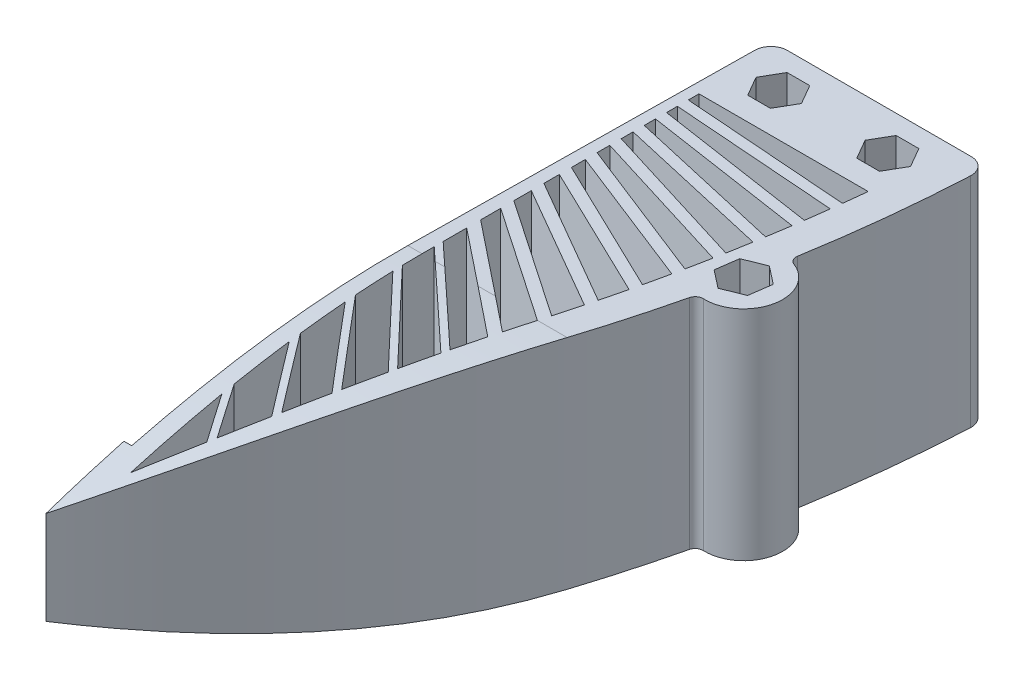
SolidWorks part; units mm, degrees
material "6061 合金"
ref_plane "前视基准面" through (0, 0, 0) normal (0, 0, 1) x (1, 0, 0)
ref_plane "上视基准面" through (0, 0, 0) normal (0, 1, 0) x (1, 0, 0)
ref_plane "右视基准面" through (0, 0, 0) normal (1, 0, 0) x (0, 0, -1)
other "Configuration Table"
sketch "草图3" plane through (0, 0, 0) normal (0, 1, 0) x (1, 0, 0)
  line B0 (0, 120.3647) -> (0, 1)
  line B1 (36.724, 123.3647) -> (3, 123.3647)
  line B2 (6.4046, 13.5169) -> (1.8, 20.8875)
  line B3 (1.8, 20.8875) -> (1.8, 4.167)
  line B4 (10.1087, 21.7103) -> (1.8, 33.2384)
  line B5 (1.8, 23.1524) -> (7.0103, 14.8122)
  line B6 (1.8, 33.2384) -> (1.8, 23.1524)
  line B7 (13.3609, 29.5129) -> (1.8, 43.5031)
  line B8 (1.8, 35.2908) -> (10.6622, 22.9946)
  line B9 (1.8, 43.5031) -> (1.8, 35.2908)
  line B10 (16.224, 36.9613) -> (1.8, 52.2374)
  line B11 (1.8, 45.3869) -> (13.8664, 30.785)
  line B12 (1.8, 52.2374) -> (1.8, 45.3869)
  line B13 (18.7509, 44.0926) -> (1.8, 59.8201)
  line B14 (1.8, 53.9853) -> (16.6853, 38.2206)
  line B15 (1.8, 59.8201) -> (1.8, 53.9853)
  line B16 (20.8682, 50.5668) -> (1.8, 65.7724)
  line B17 (1.8, 61.457) -> (19.1715, 45.3393)
  line B18 (1.8, 65.7724) -> (1.8, 61.457)
  line B19 (22.9742, 57.5717) -> (1.8, 72.0074)
  line B20 (1.8, 68.3304) -> (21.5044, 52.6174)
  line B21 (1.8, 72.0074) -> (1.8, 68.3304)
  line B22 (24.8276, 64.329) -> (1.8, 77.6234)
  line B23 (1.8, 74.4279) -> (23.5489, 59.6005)
  line B24 (1.8, 77.6234) -> (1.8, 74.4279)
  line B25 (26.4619, 70.8851) -> (1.8, 82.7612)
  line B26 (1.8, 79.9327) -> (25.3458, 66.3392)
  line B27 (1.8, 82.7612) -> (1.8, 79.9327)
  line B28 (27.9039, 77.2845) -> (1.8, 87.5291)
  line B29 (1.8, 84.981) -> (26.9277, 72.8807)
  line B30 (1.8, 87.5291) -> (1.8, 84.981)
  line B31 (29.1751, 83.5691) -> (1.8, 92.0128)
  line B32 (1.8, 89.6776) -> (28.3208, 79.2693)
  line B33 (1.8, 92.0128) -> (1.8, 89.6776)
  line B34 (30.2921, 89.7796) -> (1.8, 96.2825)
  line B35 (1.8, 94.1058) -> (29.5459, 85.5477)
  line B36 (1.8, 96.2825) -> (1.8, 94.1058)
  line B37 (31.2672, 95.956) -> (1.8, 100.3973)
  line B38 (1.8, 98.334) -> (30.6188, 91.7565)
  line B39 (1.8, 100.3973) -> (1.8, 98.334)
  line B40 (32.1089, 102.1377) -> (1.8, 104.409)
  line B41 (1.8, 102.4199) -> (31.5513, 97.9358)
  line B42 (1.8, 104.409) -> (1.8, 102.4199)
  line B43 (32.8223, 108.3647) -> (1.8, 108.3647)
  line B44 (1.8, 106.4146) -> (32.3512, 104.1252)
  line B45 (1.8, 108.3647) -> (1.8, 106.4146)
  line B46 (1.8, 110.3647) -> (33.0229, 110.3647)
  line B47 (1.8, 113.3647) -> (1.8, 110.3647)
  line B48 (33.298, 113.3647) -> (1.8, 113.3647)
  arc B49 (1.8, 4.167) -> (6.4046, 13.5169) centre (-259.6074, 138.7114) ccw
  arc B50 (7.0103, 14.8122) -> (10.1087, 21.7103) centre (-259.6074, 138.7114) ccw
  arc B51 (10.6622, 22.9946) -> (13.3609, 29.5129) centre (-259.6074, 138.7114) ccw
  arc B52 (0, 1) -> (1.8457, 0.4664) centre (1, 1) ccw
  arc B53 (1.8457, 0.4664) -> (33.5274, 76.1799) centre (-207.4276, 132.52) ccw
  arc B54 (35.9053, 78.4473) -> (33.5274, 76.1799) centre (36.4486, 75.4969) ccw
  arc B55 (35.9053, 78.4473) -> (37.7492, 87.541) centre (35, 83.3647) ccw
  arc B56 (36.4422, 90.5556) -> (37.7492, 87.541) centre (39.3987, 90.0468) ccw
  arc B57 (36.4422, 90.5556) -> (39.7203, 120.2155) centre (-207.4276, 132.52) ccw
  arc B58 (39.7203, 120.2155) -> (36.724, 123.3647) centre (36.724, 120.3647) ccw
  arc B59 (3, 123.3647) -> (0, 120.3647) centre (3, 120.3647) ccw
  arc B60 (13.8664, 30.785) -> (16.224, 36.9613) centre (-259.6074, 138.7114) ccw
  arc B61 (16.6853, 38.2206) -> (18.7509, 44.0926) centre (-259.6074, 138.7114) ccw
  arc B62 (19.1715, 45.3393) -> (20.8682, 50.5668) centre (-259.6074, 138.7114) ccw
  arc B63 (21.5044, 52.6174) -> (22.9742, 57.5717) centre (-259.6074, 138.7114) ccw
  arc B64 (23.5489, 59.6005) -> (24.8276, 64.329) centre (-259.6074, 138.7114) ccw
  arc B65 (25.3458, 66.3392) -> (26.4619, 70.8851) centre (-259.6074, 138.7114) ccw
  arc B66 (26.9277, 72.8807) -> (27.9039, 77.2845) centre (-259.6074, 138.7114) ccw
  arc B67 (28.3208, 79.2693) -> (29.1751, 83.5691) centre (-259.6074, 138.7114) ccw
  circle B68 centre (35, 83.3647) radius 2
  arc B69 (29.5459, 85.5477) -> (30.2921, 89.7796) centre (-259.6074, 138.7114) ccw
  arc B70 (30.6188, 91.7565) -> (31.2672, 95.956) centre (-259.6074, 138.7114) ccw
  arc B71 (31.5513, 97.9358) -> (32.1089, 102.1377) centre (-259.6074, 138.7114) ccw
  arc B72 (32.3512, 104.1252) -> (32.8223, 108.3647) centre (-259.6074, 138.7114) ccw
  arc B73 (33.0229, 110.3647) -> (33.298, 113.3647) centre (-259.6074, 138.7114) ccw
  circle B74 centre (35, 118.3647) radius 2
  circle B75 centre (5, 118.3647) radius 2
sketch_block_instance "umi-1"
sketch_block "umi"
extrude "凸台-拉伸2" add sketch "草图3" along normal blind 40
scale "缩放比例2" scale about centroid uniform scaling yes scale factor 0.7
sketch "草图7" plane through (0, 34, 0) normal (0, 1, 0) x (1, 0, 0)
  line L1 (3.2917, 19.3564) -> (3.2917, 29.3564)
  line L2 (3.2917, 29.3564) -> (4.2917, 29.3564)
  line L3 (4.2917, 29.3564) -> (5.2917, 108.3072)
  line L4 (5.2917, 108.3072) -> (5.2917, 24.752) construction
  line L5 (5.2917, 108.3072) -> (5.2917, 24.752)
  arc A0 (6.5837, 24.3784) -> (28.7609, 77.3779) centre (-139.9076, 116.816) ccw construction
  arc A1 (3.2917, 19.3564) -> (6.5837, 24.3784) centre (-139.9076, 116.816) ccw
  arc A4 (5.2917, 24.752) -> (6.5837, 24.3784) centre (5.9917, 24.752) ccw construction
  arc A5 (5.2917, 24.752) -> (6.5837, 24.3784) centre (5.9917, 24.752) ccw
  dimension "D1" = 2
  dimension "D2" = 1
  dimension "D3" = 10
extrude "凸台-拉伸3" add sketch "草图7" against normal up to surface (28 mm away) up to face at (17.3284, 6, -98.8239)
sketch "草图6" plane through (0, 34, 0) normal (0, 1, 0) x (1, 0, 0)
  circle A0 centre (8.7917, 106.9072) radius 1.5
  circle A1 centre (29.7917, 106.9072) radius 1.5
  circle A2 centre (29.7917, 82.4072) radius 1.5
  dimension "D1" = 3
  dimension "D2" = 3
  dimension "D3" = 3
extrude "切除-拉伸4" cut sketch "草图6" against normal blind 30
sketch "草图9" plane through (0, 34, 0) normal (0, 1, 0) x (1, 0, 0)
  circle A0 centre (29.7917, 106.9072) radius 1.5 construction
  circle A1 centre (8.7917, 106.9072) radius 1.5 construction
  circle A2 centre (29.7917, 106.9072) radius 1.5
  circle A3 centre (8.7917, 106.9072) radius 1.5
extrude "凸台-拉伸5" add sketch "草图9" against normal up to surface (28 mm away) up to face at (8.7917, 6, -105.4072)
sketch "草图17" plane through (0, 34, 0) normal (0, 1, 0) x (1, 0, 0)
  line L3 (28.6003, 103.4072) -> (6.5517, 103.4072)
  line L4 (6.5517, 101.3072) -> (28.4078, 101.3072)
  line L5 (6.5517, 103.4072) -> (6.5517, 101.3072)
  line L6 (28.6003, 103.4072) -> (6.5517, 103.4072)
  line L7 (6.5517, 101.3072) -> (28.4078, 101.3072)
  line L8 (6.5517, 103.4072) -> (6.5517, 101.3072)
  arc A0 (28.7956, 77.5075) -> (30.7828, 87.308) centre (29.7917, 82.4072) ccw
  arc A1 (28.4078, 101.3072) -> (28.6003, 103.4072) centre (-176.4334, 121.1499) ccw
  arc A2 (28.4078, 101.3072) -> (28.6003, 103.4072) centre (-176.4334, 121.1499) ccw
  arc A5 (30.4255, 78.9651) -> (28.7609, 77.3779) centre (30.8057, 76.8998) ccw construction
  arc A6 (30.4255, 78.9651) -> (31.7162, 85.3307) centre (29.7917, 82.4072) ccw construction
  arc A7 (30.8013, 87.4409) -> (31.7162, 85.3307) centre (32.8708, 87.0847) ccw construction
  arc A8 (30.4255, 78.9651) -> (28.7956, 77.5075) centre (30.8057, 76.8998) ccw
  arc A9 (30.4255, 78.9651) -> (31.7162, 85.3307) centre (29.7917, 82.4072) ccw
  arc A10 (30.7828, 87.308) -> (31.7162, 85.3307) centre (32.8708, 87.0847) ccw
  dimension "D2" = 10
  dimension "D1" = 0
extrude "凸台-拉伸6" add sketch "草图17" against normal up to surface (28 mm away)
sketch "草图12" plane through (0, 34, 0) normal (0, 1, 0) x (1, 0, 0)
  line L0 (30.9985, 110.4072) -> (7.3917, 110.4072) construction
  circle A0 centre (11.2917, 105.4072) radius 1.5
  circle A1 centre (25.2917, 105.4072) radius 1.5
  dimension "D1" = 3
  dimension "D2" = 5
  dimension "D3" = 6
  dimension "D4" = 3
  dimension "D6" = 14
extrude "切除-拉伸6" cut sketch "草图12" against normal blind 37
sketch "草图18" plane through (0, 34, 0) normal (0, 1, 0) x (1, 0, 0)
  line L0 (30.9985, 110.4072) -> (7.3917, 110.4072) construction
  line L1 (12.7495, 102.8822) -> (14.2073, 105.4072)
  line L2 (14.2073, 105.4072) -> (12.7495, 107.9322)
  line L3 (12.7495, 107.9322) -> (9.8339, 107.9322)
  line L4 (9.8339, 107.9322) -> (8.3761, 105.4072)
  line L5 (8.3761, 105.4072) -> (9.8339, 102.8822)
  line L6 (9.8339, 102.8822) -> (12.7495, 102.8822)
  line L7 (26.7495, 102.8822) -> (28.2073, 105.4072)
  line L8 (28.2073, 105.4072) -> (26.7495, 107.9322)
  line L9 (26.7495, 107.9322) -> (23.8339, 107.9322)
  line L10 (23.8339, 107.9322) -> (22.3761, 105.4072)
  line L11 (22.3761, 105.4072) -> (23.8339, 102.8822)
  line L12 (23.8339, 102.8822) -> (26.7495, 102.8822)
  line L14 (32.495, 83.4994) -> (30.1975, 85.2945)
  line L15 (30.1975, 85.2945) -> (27.4942, 84.2023)
  line L16 (27.4942, 84.2023) -> (27.0884, 81.315)
  line L17 (27.0884, 81.315) -> (29.386, 79.52)
  line L18 (29.386, 79.52) -> (32.0893, 80.6122)
  line L19 (32.0893, 80.6122) -> (32.495, 83.4994)
  circle A0 centre (11.2917, 105.4072) radius 2.525 construction
  circle A1 centre (25.2917, 105.4072) radius 2.525 construction
  circle A2 centre (29.7917, 82.4072) radius 2.525 construction
  dimension "D1" = 5.05
  dimension "D2" = 5.05
  dimension "D3" = 5.05
  dimension "D4" = 98
extrude "切除-拉伸8" cut sketch "草图18" against normal blind 30
fillet "圆角1" radius 1 2 edges at (28.7956, 20, -77.5075) (30.7828, 20, -87.308)
sketch "草图13" plane through (3.2917, 0, 0) normal (-1, 0, 0) x (0, 0, 1)
  line L0 (-108.3072, 20) -> (-19.3564, 20) construction
  line L1 (-108.3072, 34) -> (-108.3072, 6) construction
  line L2 (-19.3564, 6) -> (-19.3564, 34) construction
  line L3 (-108.3072, 34) -> (-29.3564, 34) construction
  line L4 (-64.3564, 34) -> (-19.3564, 34)
  line L5 (-19.3564, 34) -> (-19.3564, 26)
  line L6 (-19.3564, 6) -> (-19.3564, 14)
  line L7 (-64.3564, 6) -> (-19.3564, 6)
  line L8 (-54.7624, 34) -> (-88.5309, 34) construction
  spline S0 degree 2 poles (-64.3564, 34) (-43.2511, 34) (-19.3564, 26) knots 0.085144 0.085144 0.085144 1 1 1
  spline S1 degree 2 poles (-64.3564, 6) (-43.2511, 6) (-19.3564, 14) knots 0.085144 0.085144 0.085144 1 1 1
  line M6 (-19.3564, 6) -> (-19.3564, 34)
  line M7 (-19.3564, 34) -> (-29.3564, 34)
  line M8 (-29.3564, 34) -> (-29.3564, 6)
  dimension "D2" = 45
  dimension "D1" = 6
extrude "切除-拉伸7" cut sketch "草图13" against normal blind 37 contours L4 S0 M8 | S0 M8 M6 M7 | S1 L6 L7
